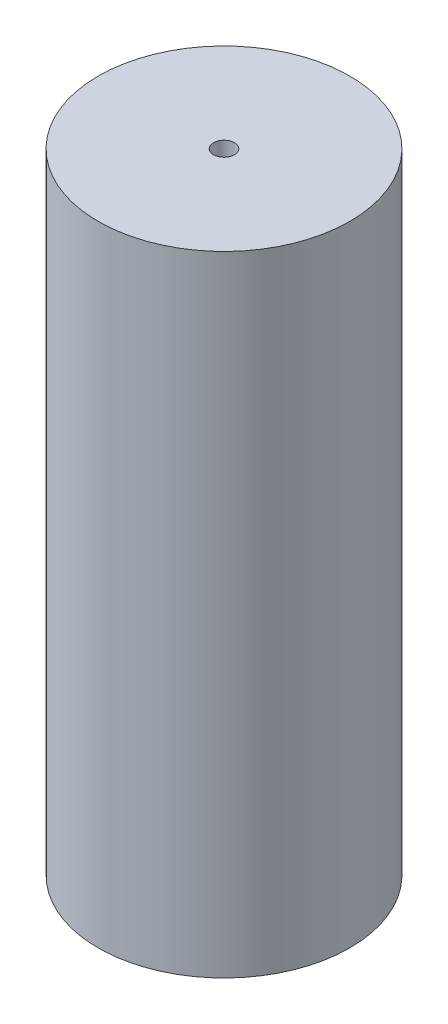
SolidWorks part; units mm, degrees
ref_plane "Front Plane" through (0, 0, 0) normal (0, 0, 1) x (1, 0, 0)
ref_plane "Top Plane" through (0, 0, 0) normal (0, 1, 0) x (1, 0, 0)
ref_plane "Right Plane" through (0, 0, 0) normal (1, 0, 0) x (0, 0, -1)
sketch "Sketch1" plane through (0, 0, 0) normal (0, 0, 1) x (1, 0, 0)
  line L0 (0, 0) -> (0, 18.9524) construction
  line L1 (0, 15) -> (-3, 15)
  line L2 (-3, 15) -> (-3, 0)
  line L3 (-3, 0) -> (-2, 0)
  line L4 (-2, 0) -> (-2, 12)
  line L5 (-2, 12) -> (0, 12)
  line L6 (0, 15) -> (0, 12)
  dimension "D1" = 3
  dimension "D2" = 1
  dimension "D3" = 15
  dimension "D4" = 3
revolve "Revolve1" add sketch "Sketch1" angle 360 about L0
sketch "Sketch2" plane through (0, 15, 0) normal (0, 1, 0) x (1, 0, 0)
  circle A0 centre (0, 0) radius 0.25
  dimension "D1" = 0.5
extrude "Cut-Extrude1" cut sketch "Sketch2" against normal through all
